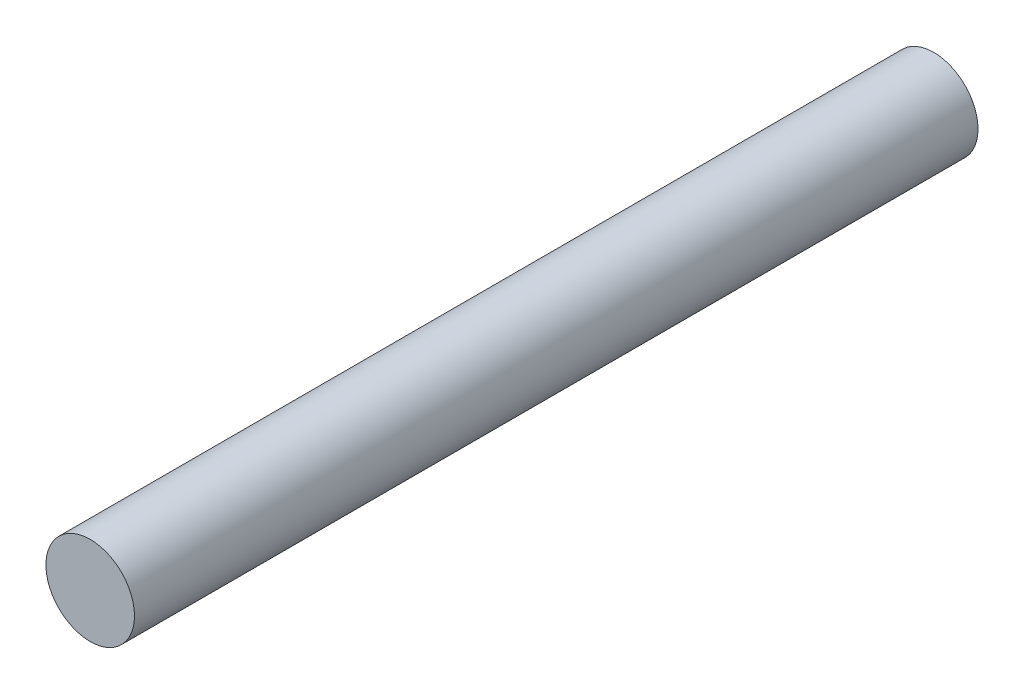
SolidWorks part; units mm, degrees
ref_plane "Piano frontale" through (0, 0, 0) normal (1, 0, 0) x (0, 1, 0)
ref_plane "Piano superiore" through (0, 0, 0) normal (0, 0, 1) x (0, 1, 0)
ref_plane "Piano destro" through (0, 0, 0) normal (0, 1, 0) x (-1, 0, 0)
sketch "Schizzo1" plane through (0, 0, 0) normal (0, 0, 1) x (0, 1, 0)
  circle A0 centre (0, 0) radius 2.1
  dimension "D1" = 4.2
extrude "Estrusione-Estrusione1" add sketch "Schizzo1" along normal blind 40
